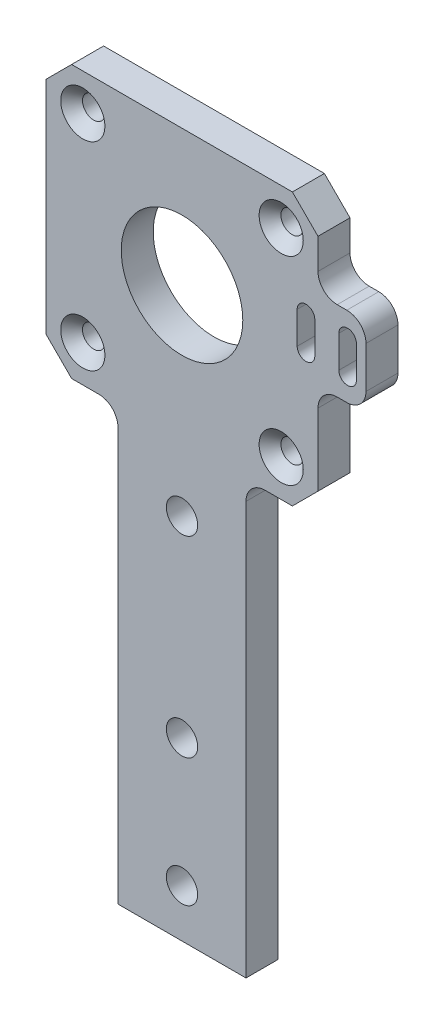
SolidWorks part; units mm, degrees
ref_plane "Спереди" through (0, 0, 0) normal (0, 0, 1) x (1, 0, 0)
ref_plane "Сверху" through (0, 0, 0) normal (0, 1, 0) x (1, 0, 0)
ref_plane "Справа" through (0, 0, 0) normal (1, 0, 0) x (0, 0, -1)
sketch "Эскиз1" plane through (0, 0, 0) normal (0, 0, 1) x (1, 0, 0)
  line L1 (-21.25, -21.25) -> (21.25, -21.25)
  line L2 (-21.25, -21.25) -> (-21.25, 21.25)
  line L3 (-21.25, 21.25) -> (21.25, 21.25)
  line L4 (21.25, -21.25) -> (21.25, 21.25)
  line L5 (-21.25, -21.25) -> (21.25, 21.25) construction
  line L6 (-21.25, 21.25) -> (21.25, -21.25) construction
  line L7 (-10, -21.25) -> (10, -21.25)
  line L8 (-10, -21.25) -> (-10, -88.75)
  line L9 (-10, -88.75) -> (10, -88.75)
  line L10 (10, -21.25) -> (10, -88.75)
  line L11 (18, 0.75) -> (20.75, 0.75)
  line L12 (18, 0.75) -> (18, 5.75)
  line L13 (18, 5.75) -> (20.75, 5.75)
  line L14 (20.75, 0.75) -> (20.75, 5.75)
  line L15 (24.5, 0.75) -> (27.25, 0.75)
  line L16 (24.5, 0.75) -> (24.5, 5.75)
  line L17 (24.5, 5.75) -> (27.25, 5.75)
  line L18 (27.25, 0.75) -> (27.25, 5.75)
  line L19 (21.25, 9.5) -> (28.75, 9.5)
  line L20 (21.25, 9.5) -> (21.25, -3)
  line L21 (21.25, -3) -> (28.75, -3)
  line L22 (28.75, 9.5) -> (28.75, -3)
  circle A0 centre (-15.5, 15.5) radius 1.75
  circle A1 centre (15.5, 15.5) radius 1.75
  circle A2 centre (15.5, -15.5) radius 1.75
  circle A3 centre (-15.5, -15.5) radius 1.75
  circle A4 centre (0, 0) radius 9.5
  circle A5 centre (0, -31.25) radius 2.45
  circle A6 centre (0, -61.25) radius 2.45
  circle A7 centre (0, -81.25) radius 2.45
  circle A8 centre (19.375, 0.75) radius 1.375
  circle A9 centre (25.875, 0.75) radius 1.375
  circle A12 centre (19.375, 5.75) radius 1.375
  circle A13 centre (25.875, 5.75) radius 1.375
  point P0 (0, 0)
  point P17 (0, 0)
  point P31 (0, -88.75)
  point P42 (27.25, 3.25)
  point P45 (28.75, 3.25)
  dimension "D2" = 3.5
  dimension "D5" = 19
  dimension "D7" = 4.9
  dimension "D12" = 6.5
  dimension "D13" = 2.75
  dimension "D1" = 42.5
  dimension "D4" = 31
  dimension "D6" = 20
  dimension "D8" = 30
  dimension "D9" = 20
  dimension "D10" = 10
  dimension "D11" = 67.5
  dimension "D14" = 5
  dimension "D15" = 15.5
  dimension "D16" = 18
  dimension "D17" = 12.5
  dimension "D18" = 7.5
  dimension "D3" = 4
extrude "Бобышка-Вытянуть1" add sketch "Эскиз1" along normal blind 5 contours L1 L4 L3 L2 A4 A3 A2 A1 A0 | L10 L1 L8 L9 | L22 L19 L4 L21 A13 L18 A9 L16
chamfer "Фаска1" distance 4 angle 45 4 edges at (-21.25, -21.25, 2.5) (-21.25, 21.25, 2.5) (21.25, 21.25, 2.5) (21.25, -21.25, 2.5)
fillet "Скругление1" radius 3 6 edges at (-10, -21.25, 2.5) (10, -21.25, 2.5) (21.25, -3, 2.5) (28.75, -3, 2.5) (28.75, 9.5, 2.5) (21.25, 9.5, 2.5)
chamfer "Фаска2" distance 1.7 4 edges at (-13.75, -15.5, 5) (17.25, -15.5, 5) (-13.75, 15.5, 5) (17.25, 15.5, 5)
sketch "Эскиз2" plane through (0, 0, 0) normal (0, 0, -1) x (-1, 0, 0)
  line L77 (-28.25, 5.75) -> (-28.25, 0.75)
  line L78 (-23.5, 0.75) -> (-23.5, 5.75)
  line L79 (-28.25, 5.75) -> (-28.25, 0.75)
  line L80 (-23.5, 0.75) -> (-23.5, 5.75)
  line L85 (-17, 0.75) -> (-17, 5.75)
  line L86 (-21.75, 5.75) -> (-21.75, 0.75)
  line L87 (-17, 0.75) -> (-17, 5.75)
  line L88 (-21.75, 5.75) -> (-21.75, 0.75)
  arc A52 (-28.25, 0.75) -> (-23.5, 0.75) centre (-25.875, 0.75) ccw
  arc A53 (-23.5, 5.75) -> (-28.25, 5.75) centre (-25.875, 5.75) ccw
  arc A54 (-28.25, 0.75) -> (-23.5, 0.75) centre (-25.875, 0.75) ccw
  arc A55 (-23.5, 5.75) -> (-28.25, 5.75) centre (-25.875, 5.75) ccw
  arc A62 (-21.75, 0.75) -> (-17, 0.75) centre (-19.375, 0.75) ccw
  arc A63 (-17, 5.75) -> (-21.75, 5.75) centre (-19.375, 5.75) ccw
  arc A64 (-21.75, 0.75) -> (-17, 0.75) centre (-19.375, 0.75) ccw
  arc A65 (-17, 5.75) -> (-21.75, 5.75) centre (-19.375, 5.75) ccw
  dimension "D1" = 1
  dimension "D2" = 1
extrude "Вырез-Вытянуть1" cut sketch "Эскиз2" against normal blind 2
